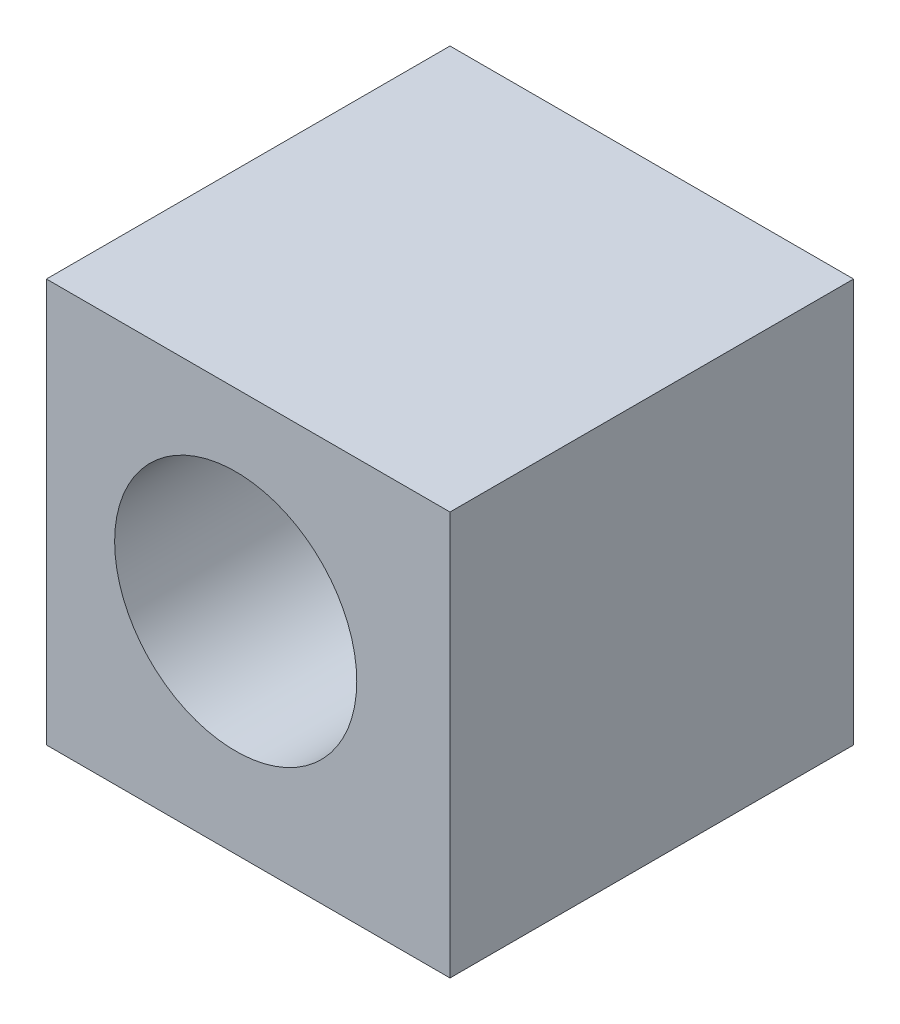
SolidWorks part; units mm, degrees
material "1060 Alloy"
ref_plane "Front Plane" through (0, 0, 0) normal (0, 0, 1) x (1, 0, 0)
ref_plane "Top Plane" through (0, 0, 0) normal (0, 1, 0) x (1, 0, 0)
ref_plane "Right Plane" through (0, 0, 0) normal (1, 0, 0) x (0, 0, -1)
sketch "Sketch1" plane through (0, 0, 0) normal (0, 0, 1) x (1, 0, 0)
  line L1 (0, 0) -> (50, 0)
  line L2 (0, 0) -> (0, 50)
  line L3 (0, 50) -> (50, 50)
  line L4 (50, 0) -> (50, 50)
  dimension "D1" = 50
  dimension "D2" = 50
extrude "Boss-Extrude1" add sketch "Sketch1" along normal blind 50
sketch "Sketch2" plane through (0, 0, 50) normal (0, 0, 1) x (1, 0, 0)
  circle A0 centre (23.4487, 26.0631) radius 15
  dimension "D1" = 30
extrude "Cut-Extrude1" cut sketch "Sketch2" against normal through all
